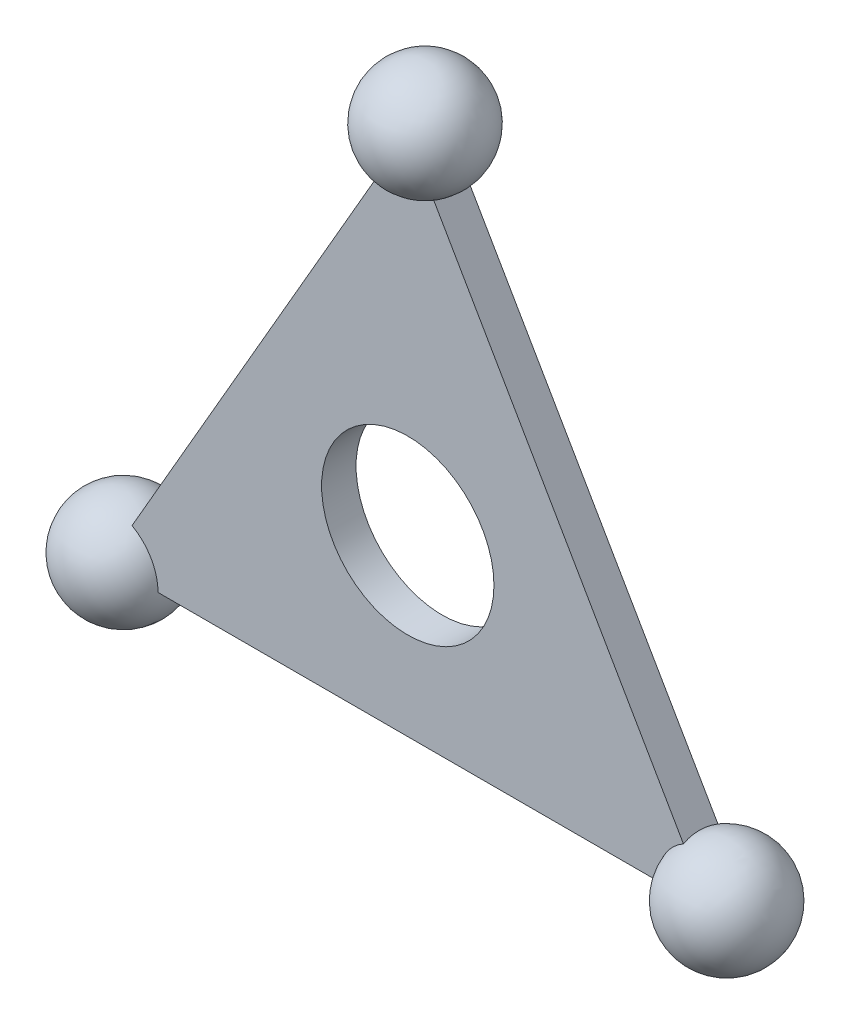
SolidWorks part; units mm, degrees
ref_plane "Plan de face" through (0, 0, 0) normal (0, 0, 1) x (1, 0, 0)
ref_plane "Plan de dessus" through (0, 0, 0) normal (0, 1, 0) x (1, 0, 0)
ref_plane "Plan de droite" through (0, 0, 0) normal (1, 0, 0) x (0, 0, -1)
sketch "Esquisse1" plane through (0, 0, 0) normal (0, 0, 1) x (1, 0, 0)
  line L0 (0, 0) -> (0, 40.4145) construction
  line L1 (0, 0) -> (-35, -20.2073) construction
  line L2 (0, 0) -> (35, -20.2073) construction
  line L3 (0, 40.4145) -> (-35, -20.2073)
  line L4 (-35, -20.2073) -> (35, -20.2073)
  line L5 (35, -20.2073) -> (0, 40.4145)
  circle A0 centre (0, 0) radius 10
  dimension "D1" = 70
  dimension "D5" = 20
  dimension "D2" = 70
  dimension "D3" = 70
  dimension "D4" = 120
extrude "Boss.-Extru.1" add sketch "Esquisse1" along normal mid plane 4
sketch "Esquisse3" plane through (0, 0, 0) normal (0, 0, 1) x (1, 0, 0)
  line L0 (0, 0) -> (0, 40.4145) construction
  line L1 (0, 46.7645) -> (0, 34.0645) construction
  line L2 (0, 46.7645) -> (0, 34.0645)
  line L3 (35, -20.2073) -> (0, 40.4145) construction
  line L5 (0, 40.4145) -> (-35, -20.2073) construction
  arc A0 (0, 46.7645) -> (0, 34.0645) centre (0, 40.4145) ccw
  dimension "D1" = 12.7
revolve "Révolution1" add sketch "Esquisse3" angle 360 about L1
pattern_circular "Répétition circulaire1" count 3 over 360 about axis through (0, 0, 0) along (0, 0, 1) of "Révolution1"
